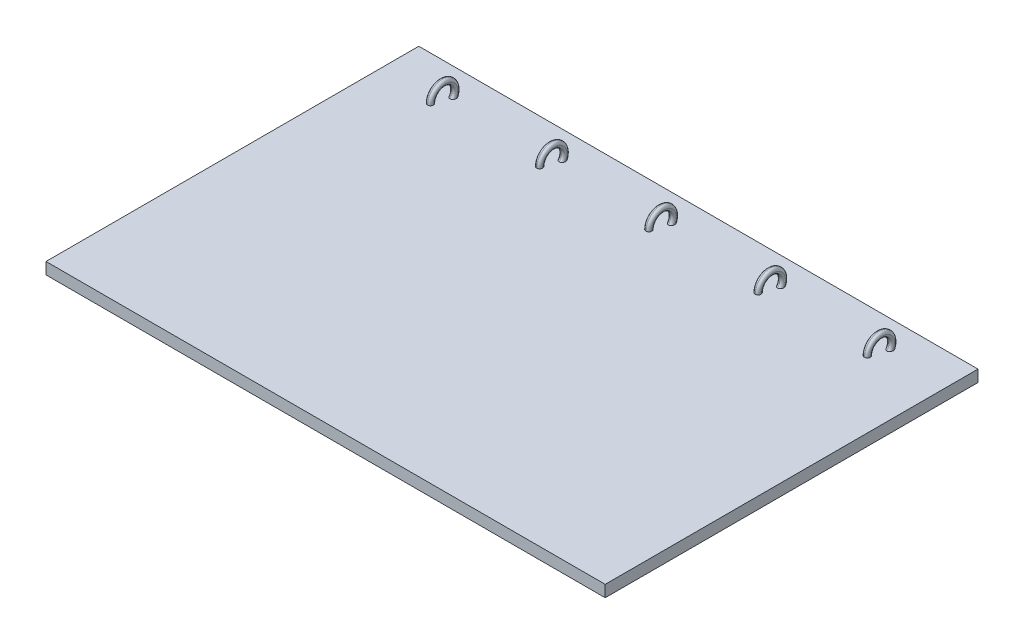
SolidWorks part; units mm, degrees
ref_plane "Front Plane" through (0, 0, 0) normal (0, 0, 1) x (1, 0, 0)
ref_plane "Top Plane" through (0, 0, 0) normal (0, 1, 0) x (1, 0, 0)
ref_plane "Right Plane" through (0, 0, 0) normal (1, 0, 0) x (0, 0, -1)
sketch "Sketch1" plane through (0, 0, 0) normal (1, 0, 0) x (0, 0, -1)
  line L0 (-50.8, 0) -> (50.8, 0)
  line L1 (50.8, 0) -> (50.8, 3.175)
  line L2 (50.8, 3.175) -> (-50.8, 3.175)
  line L3 (-50.8, 3.175) -> (-50.8, 0)
  line L4 (36.5125, 4.7625) -> (38.1, 4.7625)
  arc A0 (36.5125, 4.7625) -> (44.45, 3.175) centre (40.64, 4.7625) cw
  arc A1 (42.6228, 3.175) -> (38.1, 4.7625) centre (40.64, 4.7625) ccw
  point P4 (0, 0)
  dimension "D3" = 1.5875
  dimension "D5" = 2.54
  dimension "D1" = 3.175
  dimension "D2" = 101.6
  dimension "D4" = 1.5875
  dimension "D6" = 6.35
extrude "Boss-Extrude1" add sketch "Sketch1" along normal mid plane 152.4 contours L2 L3 L0 L1 | A1 L2 A0 L4
sketch "Sketch2" plane through (0, 3.175, 0) normal (0, 1, 0) x (1, 0, 0)
  line L18 (76.2, 44.7675) -> (-76.2, 44.7675) construction
  line L31 (76.2, 44.7675) -> (60.325, 44.7675)
  line L32 (76.2, 44.7675) -> (76.2, 36.5125)
  line L33 (76.2, 36.5125) -> (60.325, 36.5125)
  line L34 (60.325, 44.7675) -> (60.325, 36.5125)
  line L35 (-76.2, 36.5125) -> (-60.325, 36.5125)
  line L36 (-76.2, 36.5125) -> (-76.2, 44.7675)
  line L37 (-76.2, 44.7675) -> (-60.325, 44.7675)
  line L38 (-60.325, 36.5125) -> (-60.325, 44.7675)
  line L40 (60.325, 36.5125) -> (58.7375, 36.5125)
  line L41 (60.325, 36.5125) -> (60.325, 44.7675)
  line L42 (60.325, 44.7675) -> (58.7375, 44.7675)
  line L43 (58.7375, 36.5125) -> (58.7375, 44.7675)
  line L44 (-60.325, 36.5125) -> (-58.7375, 36.5125)
  line L45 (-60.325, 36.5125) -> (-60.325, 44.7675)
  line L46 (-60.325, 44.7675) -> (-58.7375, 44.7675)
  line L47 (-58.7375, 36.5125) -> (-58.7375, 44.7675)
  line L48 (58.7375, 36.5125) -> (30.5594, 36.5125)
  line L49 (58.7375, 36.5125) -> (58.7375, 44.7675)
  line L50 (58.7375, 44.7675) -> (30.5594, 44.7675)
  line L51 (30.5594, 36.5125) -> (30.5594, 44.7675)
  line L52 (-58.7375, 36.5125) -> (-30.5594, 36.5125)
  line L53 (-58.7375, 36.5125) -> (-58.7375, 44.7675)
  line L54 (-58.7375, 44.7675) -> (-30.5594, 44.7675)
  line L55 (-30.5594, 36.5125) -> (-30.5594, 44.7675)
  line L56 (0.7937, 44.7675) -> (-0.7937, 44.7675)
  line L57 (0.7937, 44.7675) -> (0.7937, 36.5125)
  line L58 (0.7937, 36.5125) -> (-0.7937, 36.5125)
  line L59 (-0.7937, 44.7675) -> (-0.7937, 36.5125)
  line L60 (30.5594, 36.5125) -> (28.9719, 36.5125)
  line L61 (30.5594, 36.5125) -> (30.5594, 44.7675)
  line L62 (30.5594, 44.7675) -> (28.9719, 44.7675)
  line L63 (28.9719, 36.5125) -> (28.9719, 44.7675)
  line L64 (28.9719, 36.5125) -> (0.7937, 36.5125)
  line L65 (28.9719, 36.5125) -> (28.9719, 44.7675)
  line L66 (28.9719, 44.7675) -> (0.7937, 44.7675)
  line L67 (0.7937, 36.5125) -> (0.7937, 44.7675)
  line L68 (-0.7937, 36.5125) -> (-28.9719, 36.5125)
  line L69 (-0.7937, 36.5125) -> (-0.7937, 44.7675)
  line L70 (-0.7937, 44.7675) -> (-28.9719, 44.7675)
  line L71 (-28.9719, 36.5125) -> (-28.9719, 44.7675)
  line L72 (-28.9719, 36.5125) -> (-30.5594, 36.5125)
  line L73 (-28.9719, 36.5125) -> (-28.9719, 44.7675)
  line L74 (-28.9719, 44.7675) -> (-30.5594, 44.7675)
  line L75 (-30.5594, 36.5125) -> (-30.5594, 44.7675)
  point P26 (0, 36.5125)
  line M18 (-76.2, 42.6228) -> (-76.2, -50.8)
  line M20 (76.2, -50.8) -> (76.2, 42.6228)
  line M21 (76.2, 42.6228) -> (-76.2, 42.6228)
  dimension "D1" = 120.65
  dimension "D2" = 1.5875
extrude "Cut-Extrude1" cut sketch "Sketch2" along normal through all contours L34 L33 M21 M20 | L31 L34 L32 M21 | L51 L48 L43 M21 | L51 L43 L50 M21 | L64 L63 L57 M21 | L63 L66 L57 M21 | L71 L68 L59 M21 | L71 L59 L70 M21 | L52 L55 L47 M21 | L55 L54 L47 M21 | L35 L38 M21 M18 | L38 L37 L36 M21
fillet "Fillet1" radius 0.762 20 edges at (-60.325, 7.1592, -41.4812) (-58.7375, 7.1592, -41.4812) (-28.9719, 7.1592, -41.4812) (-30.5594, 7.1592, -41.4812) (-0.7937, 7.1592, -41.4812) (0.7937, 7.1592, -41.4812) (28.9719, 7.1592, -41.4812) (30.5594, 7.1592, -41.4812) (58.7375, 7.1592, -41.4812) (60.325, 7.1592, -41.4812) (-60.325, 8.8098, -41.4495) (-58.7375, 8.8098, -41.4495) (-30.5594, 8.8098, -41.4495) (-28.9719, 8.8098, -41.4495) (-0.7937, 8.8098, -41.4495) (0.7937, 8.8098, -41.4495) (28.9719, 8.8098, -41.4495) (30.5594, 8.8098, -41.4495) (58.7375, 8.8098, -41.4495) (60.325, 8.8098, -41.4495)
